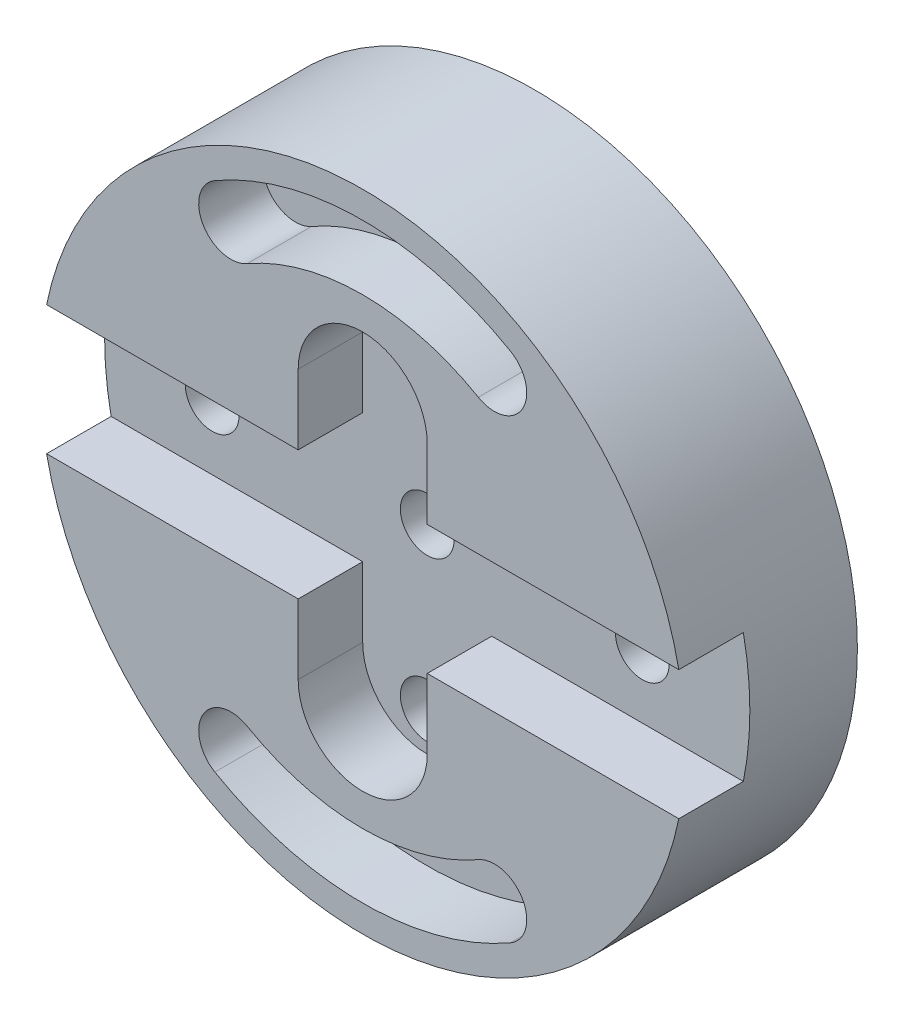
SolidWorks part; units mm, degrees
ref_plane "Front Plane" through (0, 0, 0) normal (0, 0, 1) x (1, 0, 0)
ref_plane "Top Plane" through (0, 0, 0) normal (0, 1, 0) x (1, 0, 0)
ref_plane "Right Plane" through (0, 0, 0) normal (1, 0, 0) x (0, 0, -1)
sketch "Sketch1" plane through (0, 0, 0) normal (0, 0, 1) x (1, 0, 0)
  circle A0 centre (0, 0) radius 60
  dimension "D1" = 120
extrude "Boss-Extrude1" add sketch "Sketch1" along normal blind 32 contours A0
sketch "Sketch2" plane through (0, 0, 32) normal (0, 0, 1) x (1, 0, 0)
  line L0 (12, -12) -> (72.4885, -12)
  line L1 (-72.4885, 12) -> (-12, 12)
  line L2 (-72.4885, 12) -> (-72.4885, -12)
  line L3 (-72.4885, -12) -> (-12, -12)
  line L4 (72.4885, 12) -> (72.4885, -12)
  line L5 (-72.4885, 12) -> (72.4885, -12) construction
  line L6 (-72.4885, -12) -> (72.4885, 12) construction
  line L8 (-12, 25) -> (-12, 12)
  line L10 (12, 25) -> (12, 12)
  line L11 (-12, 25) -> (12, -25) construction
  line L12 (0, 0) -> (12, 25) construction
  line L13 (12, 12) -> (72.4885, 12)
  line L14 (-12, 1.9865) -> (-12, -1.9865)
  line L15 (-12, -12) -> (-12, -25)
  line L16 (12, -12) -> (12, -25)
  line L17 (0, 0) -> (-24.5, 42.4352) construction
  line L18 (0, 0) -> (0, 49) construction
  line L19 (0, 0) -> (24.5, 42.4352) construction
  line L20 (-72.4885, 0) -> (72.4885, 0) construction
  arc A0 (12, 25) -> (-12, 25) centre (0, 25) ccw
  arc A1 (-12, -25) -> (12, -25) centre (0, -25) ccw
  arc A2 (24.5, 42.4352) -> (-24.5, 42.4352) centre (0, 0) ccw construction
  arc A8 (27.5, 47.6314) -> (-27.5, 47.6314) centre (0, 0) ccw
  arc A9 (21.5, 37.2391) -> (-21.5, 37.2391) centre (0, 0) ccw
  arc A10 (21.5, 37.2391) -> (27.5, 47.6314) centre (24.5, 42.4352) ccw
  arc A11 (-27.5, 47.6314) -> (-21.5, 37.2391) centre (-24.5, 42.4352) ccw
  point P0 (0, 0)
  point P6 (0, 0)
  point P24 (0, 49)
  dimension "D4" = 30
  dimension "D7" = 6
  dimension "D1" = 24
  dimension "D2" = 50
  dimension "D3" = 24
  dimension "D5" = 49
  dimension "D6" = 49
extrude "Cut-Extrude1" cut sketch "Sketch2" against normal blind 12 contours L2 L3 L15 A1 L16 L0 L4 L13 L10 A0 L8 L1
sketch "Sketch3" plane through (0, 0, 32) normal (0, 0, 1) x (1, 0, 0)
  line L0 (0, 0) -> (-27.5, 47.6314) construction
  line L1 (0, 0) -> (27.5, 47.6314) construction
  line L2 (0, 0) -> (0, 55) construction
  line L3 (0, 0) -> (74.6134, 0) construction
  arc A0 (21.5, -37.2391) -> (27.5, -47.6314) centre (24.5, -42.4352) cw
  arc A1 (27.5, 47.6314) -> (-27.5, 47.6314) centre (0, 0) ccw
  arc A2 (21.5, 37.2391) -> (-21.5, 37.2391) centre (0, 0) ccw
  arc A5 (-27.5, 47.6314) -> (-21.5, 37.2391) centre (-24.5, 42.4352) ccw
  arc A6 (21.5, 37.2391) -> (27.5, 47.6314) centre (24.5, 42.4352) ccw
  arc A7 (21.5, -37.2391) -> (-21.5, -37.2391) centre (0, 0) cw
  arc A8 (-27.5, -47.6314) -> (-21.5, -37.2391) centre (-24.5, -42.4352) cw
  arc A9 (27.5, -47.6314) -> (-27.5, -47.6314) centre (0, 0) cw
  point P4 (0.3902, 49.1891)
  dimension "D1" = 49
  dimension "D2" = 30
  dimension "D3" = 30
  dimension "D4" = 49
  dimension "D5" = 49
extrude "Cut-Extrude2" cut sketch "Sketch3" against normal blind 12
sketch "Sketch4" plane through (0, 0, 20) normal (0, 0, 1) x (1, 0, 0)
  line L0 (0, 13.0868) -> (0, -10.5435) construction
  line L1 (-11.5531, 0) -> (11.5402, 0) construction
  circle A0 centre (0, 0) radius 5
  arc A1 (58.7878, 12) -> (-58.7878, 12) centre (0, 0) ccw construction
  circle A2 centre (40, 0) radius 5
  circle A4 centre (0, 30) radius 5
  circle A5 centre (0, -30) radius 5
  circle A6 centre (-40, 0) radius 5
  dimension "D1" = 10
  dimension "D2" = 40
  dimension "D3" = 10
  dimension "D4" = 10
  dimension "D5" = 30
extrude "Cut-Extrude3" cut sketch "Sketch4" against normal blind 92
